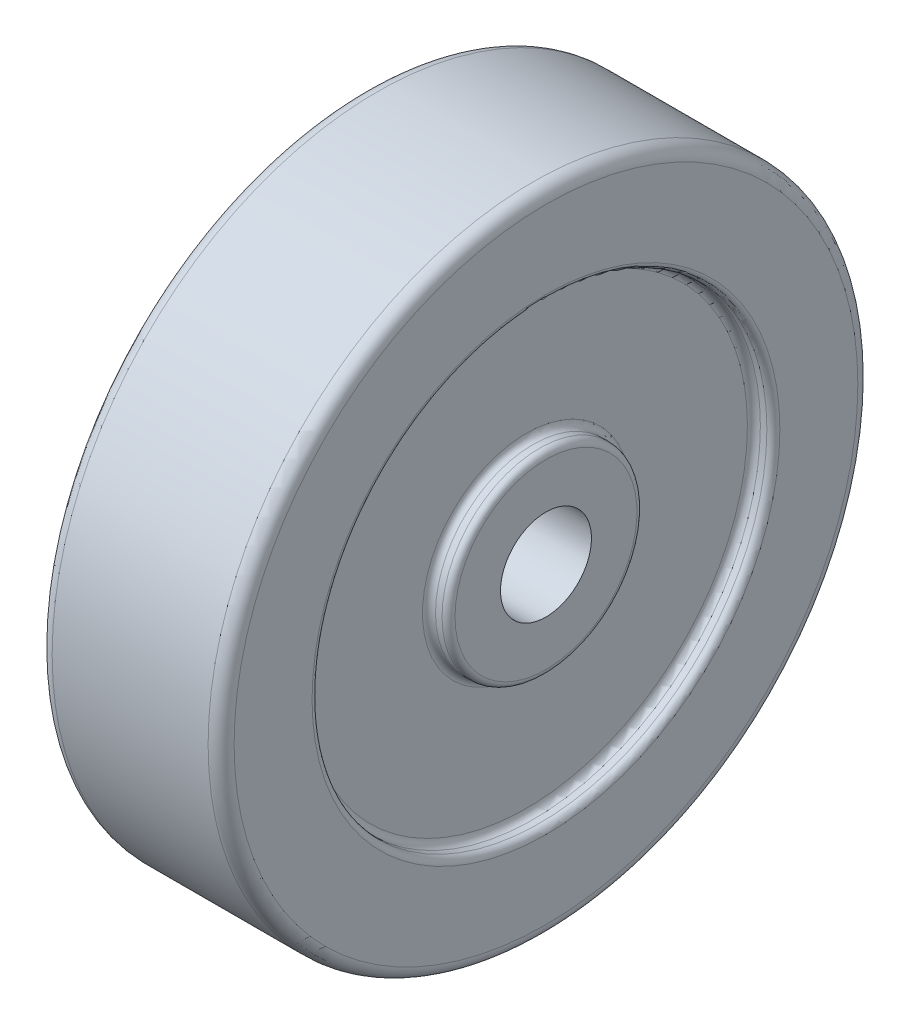
SolidWorks part; units mm, degrees
material "EPDM 60 Durometer"
ref_plane "Front Plane" through (0, 0, 0) normal (0, 0, 1) x (1, 0, 0)
ref_plane "Top Plane" through (0, 0, 0) normal (0, 1, 0) x (1, 0, 0)
ref_plane "Right Plane" through (0, 0, 0) normal (1, 0, 0) x (0, 0, -1)
sketch "Sketch1" plane through (0, 0, 0) normal (0, 0, 1) x (1, 0, 0)
  line L0 (-14, 0) -> (14, 0) construction
  line L1 (-14, 7) -> (14, 7)
  line L2 (-14, 15) -> (14, 15)
  line L3 (-14, 7) -> (-14, 15)
  line L4 (14, 7) -> (14, 15)
  line L5 (-14, 35) -> (14, 35)
  line L6 (-14, 50) -> (14, 50)
  line L7 (-14, 50) -> (-14, 35)
  line L8 (14, 50) -> (14, 35)
  line L9 (11, 35) -> (11, 15)
  line L10 (-11, 35) -> (-11, 15)
  dimension "D1" = 28
  dimension "D2" = 30
  dimension "D3" = 14
  dimension "D4" = 70
  dimension "D5" = 100
  dimension "D6" = 3
  dimension "D7" = 3
revolve "Main Wheel Body" add sketch "Sketch1" angle 360 about L0
fillet "Outer Fillets" radius 2 2 edges at (-14, 0, 50) (14, 0, 50)
fillet "Inner Fillets" radius 1 8 edges at (-14, 0, 15) (-11, 0, 15) (-11, 0, 35) (-14, 0, 35) (11, 0, 15) (14, 0, 15) (11, 0, 35) (14, 0, 35)
